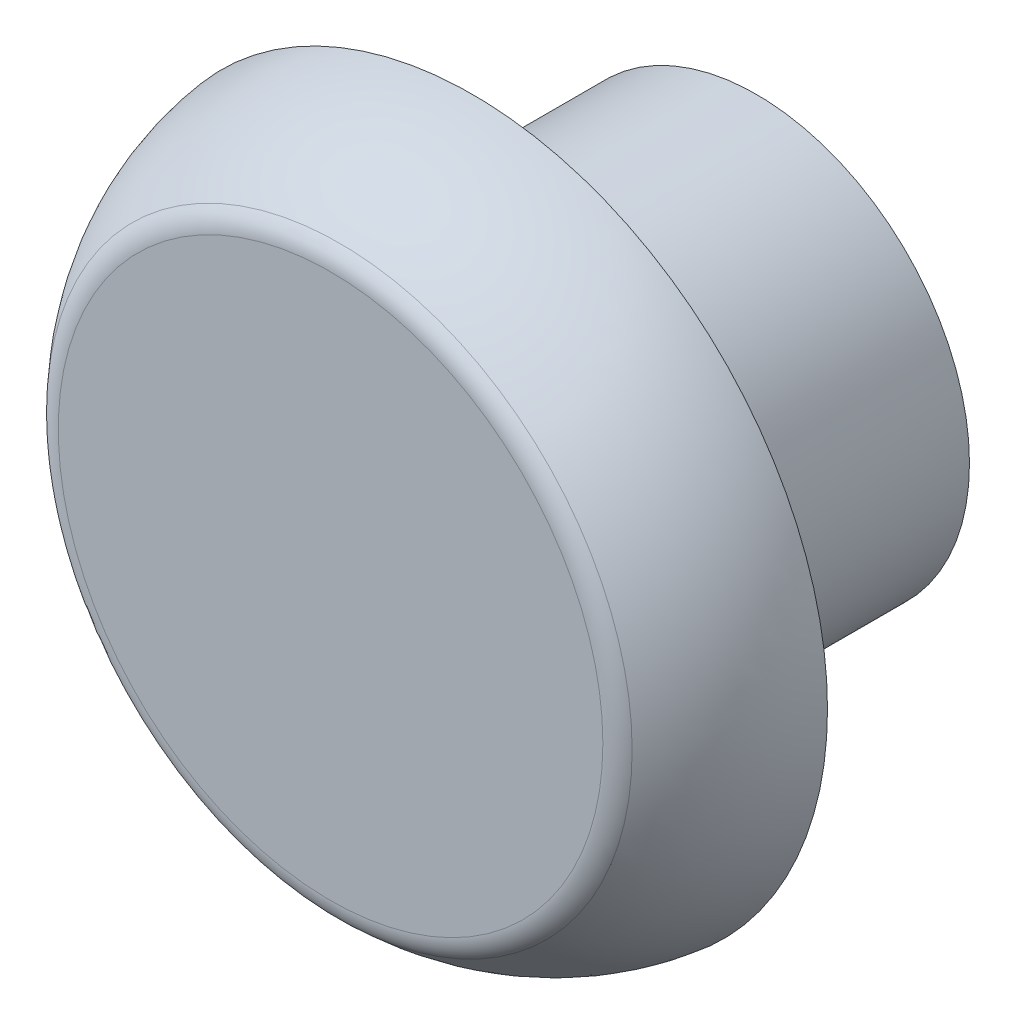
SolidWorks part; units mm, degrees
ref_plane "Alzado" through (0, 0, 0) normal (0, 0, 1) x (1, 0, 0)
ref_plane "Planta" through (0, 0, 0) normal (0, 1, 0) x (1, 0, 0)
ref_plane "Vista lateral" through (0, 0, 0) normal (1, 0, 0) x (0, 0, -1)
sketch "Croquis1" plane through (0, 0, 0) normal (0, 0, 1) x (1, 0, 0)
  circle A0 centre (0, 0) radius 1.5
extrude "Saliente-Extruir1" add sketch "Croquis1" along normal blind 2
ref_plane "Plano1" through (0, 0, 2) normal (0, 0, 1) x (1, 0, 0)
sketch "Croquis2" plane through (0, 0, 2) normal (0, 0, 1) x (1, 0, 0)
  circle A0 centre (0, 0) radius 2.5
extrude "Saliente-Extruir2" add sketch "Croquis2" along normal blind 1
sketch "Croquis3" plane through (0, 0, 0) normal (1, 0, 0) x (0, 0, -1)
  line L0 (-2, 2.5) -> (-3, 2.5)
  line L2 (-3, 2.5) -> (-3, -2.5) construction
  line L4 (-3, 2.5) -> (-3, 2)
  line L5 (0, 0) -> (-3, 0) construction
  arc A0 (-3, 2) -> (-2, 2.5) centre (-1.8241, 0.8983) cw
revolve "Cortar-Revolución1" cut sketch "Croquis3" angle 360 about L5
fillet "Redondeo3" radius 0.2 1 edges at (-2, 0, 3)
